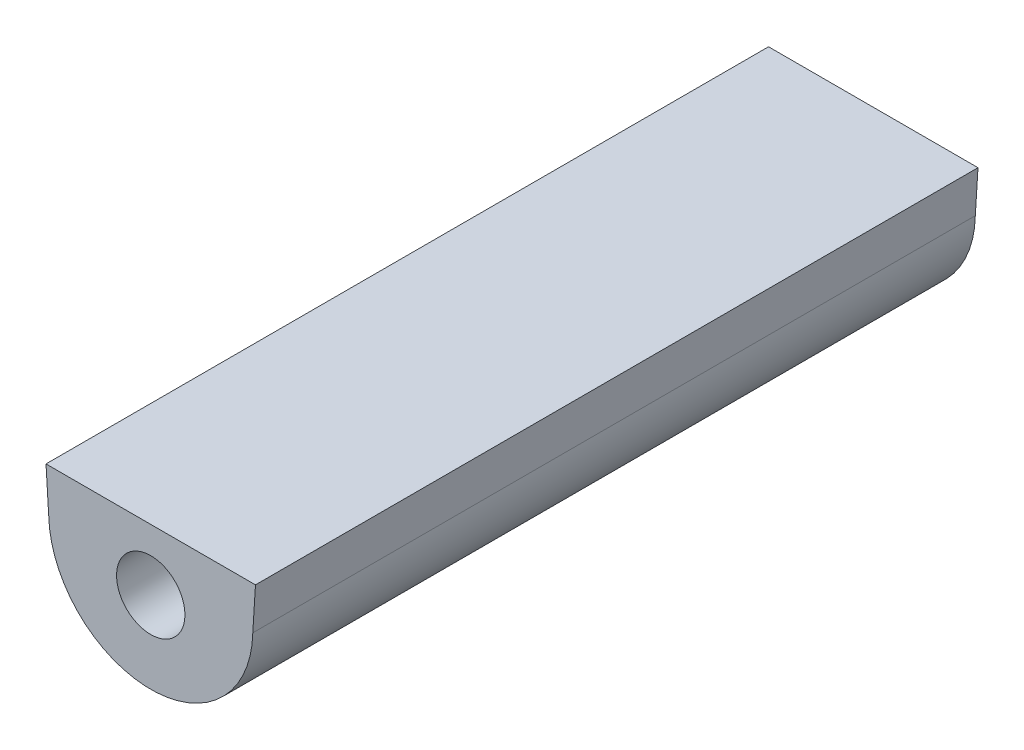
SolidWorks part; units mm, degrees
ref_plane "Front Plane" through (0, 0, 0) normal (0, 0, 1) x (1, 0, 0)
ref_plane "Top Plane" through (0, 0, 0) normal (0, 1, 0) x (1, 0, 0)
ref_plane "Right Plane" through (0, 0, 0) normal (1, 0, 0) x (0, 0, -1)
sketch "Sketch1" plane through (0, 0, 0) normal (0, 0, 1) x (1, 0, 0)
  line L0 (6.6626, -21.6753) -> (9.7812, 28.2232)
  line L1 (5.9786, 32.2709) -> (-5.3535, 32.2709)
  line L2 (-9.1561, 28.2232) -> (-6.0374, -21.6753)
  circle A0 centre (0.3126, -22.8151) radius 2.127
  circle A1 centre (0.3126, 0.0449) radius 2.127
  circle A2 centre (0.3126, 22.1109) radius 2.032
  arc A3 (-6.0374, -21.6753) -> (6.6626, -21.6753) centre (0.3126, -21.5438) ccw
  arc A4 (9.7812, 28.2232) -> (5.9786, 32.2709) centre (5.9786, 28.4609) ccw
  arc A5 (-5.3535, 32.2709) -> (-9.1561, 28.2232) centre (-5.3535, 28.4609) ccw
extrude "Boss-Extrude1" add sketch "Sketch1" along normal blind 44.958
sketch "Sketch2" plane through (0, 0, 44.958) normal (0, 0, 1) x (1, 0, 0)
  line L1 (-27.7506, -19.0051) -> (33.4121, -19.0051)
  line L2 (-27.7506, -19.0051) -> (-27.7506, 37.6523)
  line L3 (-27.7506, 37.6523) -> (33.4121, 37.6523)
  line L4 (33.4121, -19.0051) -> (33.4121, 37.6523)
  arc A0 (-6.0374, -21.6753) -> (6.6626, -21.6753) centre (0.3126, -21.5438) ccw construction
  point P7 (0.3126, -27.8951)
  dimension "D1" = 8.89
extrude "Cut-Extrude1" cut sketch "Sketch2" against normal through all
